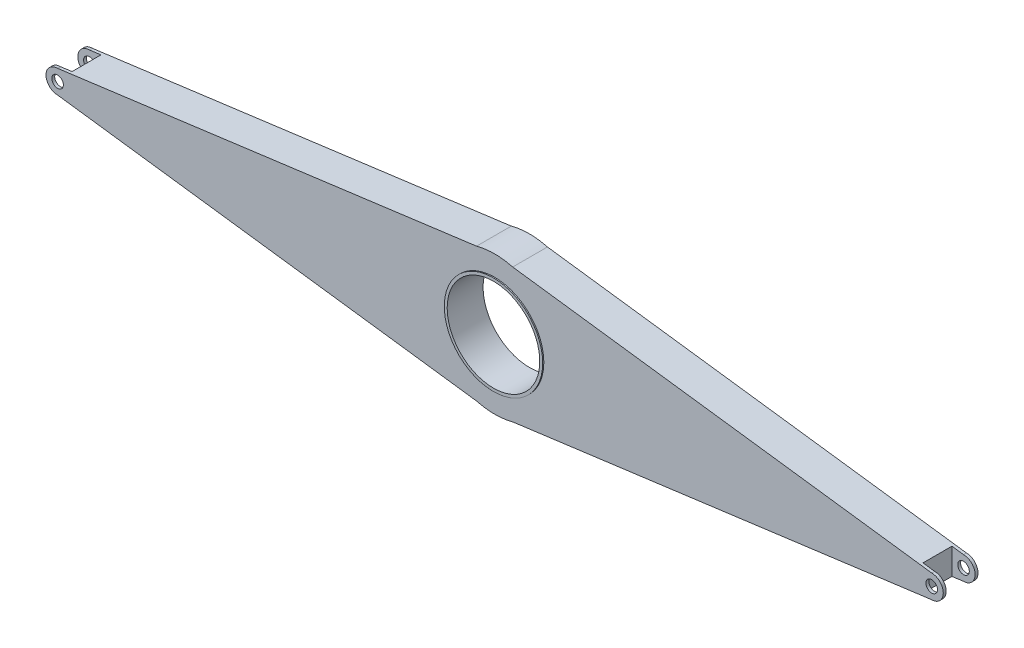
SolidWorks part; units mm, degrees
ref_plane "Front Plane" through (0, 0, 0) normal (0, 0, 1) x (1, 0, 0)
ref_plane "Top Plane" through (0, 0, 0) normal (0, 1, 0) x (1, 0, 0)
ref_plane "Right Plane" through (0, 0, 0) normal (1, 0, 0) x (0, 0, -1)
sketch "Sketch1" plane through (0, 0, 0) normal (0, 0, 1) x (1, 0, 0)
  circle A0 centre (0, 0) radius 101.6
  circle A1 centre (0, 0) radius 152.4
  dimension "D1" = 203.2
  dimension "D2" = 304.8
extrude "Boss-Extrude1" add sketch "Sketch1" along normal blind 76.2
sketch "Sketch2" plane through (0, 0, 76.2) normal (0, 0, 1) x (1, 0, 0)
  line L4 (-958.85, 25.4) -> (-39.6748, 147.1451)
  line L5 (39.6748, 147.1451) -> (958.85, 25.4)
  line L6 (-958.85, -25.4) -> (-39.6748, -147.1451)
  line L7 (39.6748, -147.1451) -> (958.85, -25.4)
  arc A0 (-958.85, 25.4) -> (-958.85, -25.4) centre (-958.85, 0) ccw
  arc A5 (958.85, -25.4) -> (958.85, 25.4) centre (958.85, 0) ccw
  arc A6 (-39.6748, 147.1451) -> (-39.6748, -147.1451) centre (0, 0) ccw
  arc A7 (39.6748, -147.1451) -> (39.6748, 147.1451) centre (0, 0) ccw
  dimension "D1" = 958.85
  dimension "D3" = 50.8
  dimension "D4" = 50.8
  dimension "D2" = 958.85
extrude "Boss-Extrude3" add sketch "Sketch2" against normal blind 76.2
sketch "Sketch7" plane through (0, 0, 76.2) normal (0, 0, 1) x (1, 0, 0)
  circle A0 centre (-958.85, 0) radius 12.7
  circle A1 centre (958.85, 0) radius 12.7
  dimension "D1" = 25.4
  dimension "D2" = 25.4
extrude "Cut-Extrude2" cut sketch "Sketch7" against normal through all
ref_plane "Plane4" through (984.25, 0, 0) normal (1, 0, 0) x (0, 0, -1)
ref_plane "Plane5" through (-984.25, 0, 0) normal (1, 0, 0) x (0, 0, -1)
sketch "Sketch8" plane through (984.25, 0, 0) normal (1, 0, 0) x (0, 0, -1)
  line L0 (-76.2, -147.1451) -> (-76.2, -25.4) construction
  line L1 (-69.85, 63.5) -> (-6.35, 63.5)
  line L2 (-69.85, 63.5) -> (-69.85, -63.5)
  line L3 (-69.85, -63.5) -> (-6.35, -63.5)
  line L4 (-6.35, 63.5) -> (-6.35, -63.5)
  dimension "D1" = 127
  dimension "D2" = 63.5
  dimension "D3" = 6.35
  dimension "D4" = 63.5
extrude "Cut-Extrude3" cut sketch "Sketch8" against normal blind 50.8
sketch "Sketch9" plane through (-984.25, 0, 0) normal (1, 0, 0) x (0, 0, -1)
  line L0 (-76.2, 25.4) -> (-76.2, -25.4) construction
  line L1 (-69.85, 63.5) -> (-6.35, 63.5)
  line L2 (-69.85, 63.5) -> (-69.85, -63.5)
  line L3 (-69.85, -63.5) -> (-6.35, -63.5)
  line L4 (-6.35, 63.5) -> (-6.35, -63.5)
  dimension "D1" = 63.5
  dimension "D2" = 127
  dimension "D3" = 6.35
  dimension "D4" = 63.5
extrude "Cut-Extrude5" cut sketch "Sketch9" along normal blind 50.8
sketch "Sketch11" plane through (0, 0, 76.2) normal (0, 0, 1) x (1, 0, 0)
  circle A0 centre (0, 0) radius 101.6
  circle A1 centre (0, 0) radius 107.95
  dimension "D1" = 215.9
extrude "Boss-Extrude4" add sketch "Sketch11" along normal blind 2.54
